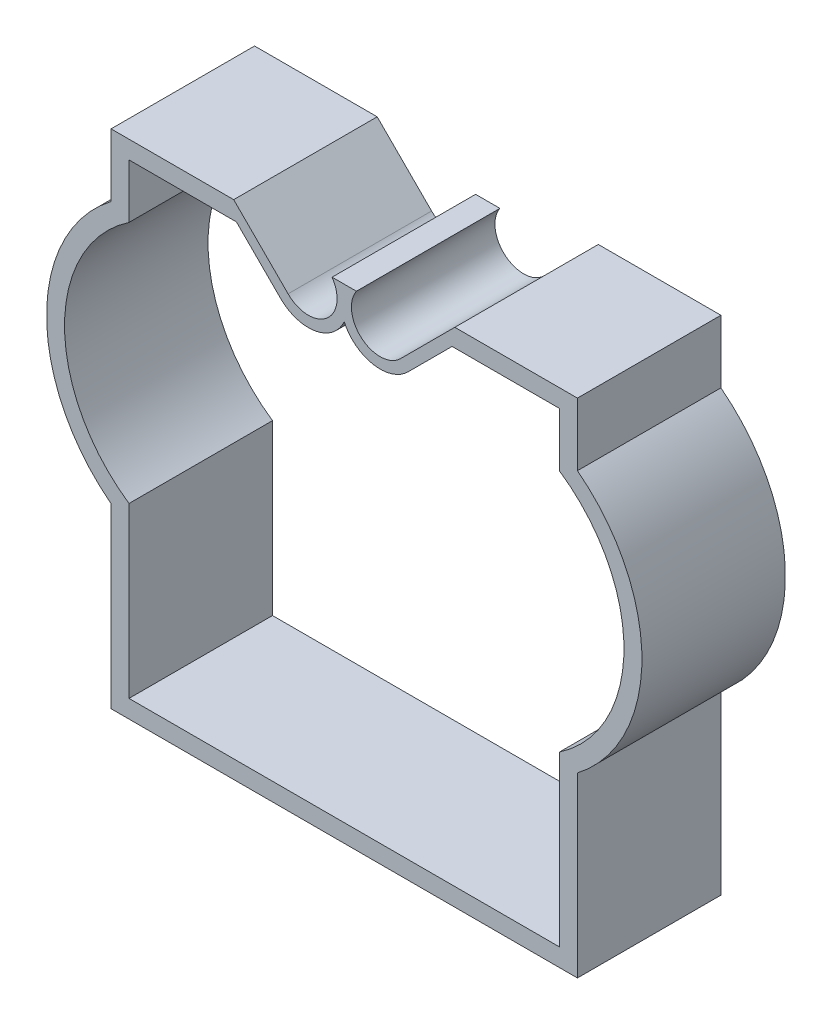
SolidWorks part; units mm, degrees
ref_plane "Ebene vorne" through (0, 0, 0) normal (0, 0, 1) x (1, 0, 0)
ref_plane "Ebene oben" through (0, 0, 0) normal (0, 1, 0) x (1, 0, 0)
ref_plane "Ebene rechts" through (0, 0, 0) normal (1, 0, 0) x (0, 0, -1)
sketch "Skizze1" plane through (0, 0, 0) normal (0, 0, 1) x (1, 0, 0)
  line L0 (-18.4884, 7.993) -> (18.4884, 7.993) construction
  line L1 (-32.5, -35) -> (32.5, -35)
  line L2 (-32.5, -35) -> (-32.5, 35)
  line L3 (-32.5, 35) -> (32.5, 35)
  line L4 (32.5, -35) -> (32.5, 35)
  line L5 (-32.5, -35) -> (32.5, 35) construction
  line L6 (-32.5, 35) -> (-7.4221, 7.993) construction
  line L7 (-30, -32.5) -> (30, -32.5)
  line L8 (-30, -32.5) -> (-30, 32.5)
  line L9 (-30, 32.5) -> (-15.0311, 32.5)
  line L10 (30, -32.5) -> (30, 32.5)
  line L11 (-30, -32.5) -> (30, 32.5) construction
  line L12 (-30, 32.5) -> (-7.3782, 7.993) construction
  line L13 (-1.6456, 1.7722) -> (32.5, -35) construction
  line L14 (-1.6505, 1.7881) -> (30, -32.5) construction
  line L15 (-15.0311, 32.5) -> (-8.8892, 26.3581)
  line L16 (-15.4098, 35) -> (-7.8286, 27.4188)
  line L17 (0, -4.7433) -> (0, -12.0184) construction
  line L18 (15.4098, 35) -> (7.8286, 27.4188)
  line L19 (15.0311, 32.5) -> (8.3305, 25.7994)
  line L20 (15.0311, 32.5) -> (30, 32.5)
  line L21 (-12.9098, 32.5) -> (12.9098, 32.5)
  arc A2 (-12.8129, 30.2818) -> (-3.0992, 25.0861) centre (-18.4884, 7.993) ccw
  circle A3 centre (-18.4884, 7.993) radius 20.5
  circle A4 centre (-5.0001, 30.2472) radius 4
  arc A5 (-1.6505, 1.7881) -> (-1.6456, 1.7722) centre (18.4884, 7.993) ccw
  arc A6 (-0.7993, 0.8659) -> (-0.7961, 0.8574) centre (18.4884, 7.993) ccw
  arc A7 (9.8435, -10.6637) -> (9.9457, -10.7108) centre (18.4884, 7.993) ccw
  arc A8 (10.6947, -11.5859) -> (10.7952, -11.6256) centre (18.4884, 7.993) ccw
  arc A9 (-0.6891, -0.7421) -> (-0.6877, -0.745) centre (18.4884, 7.993) ccw
  arc A10 (-0.3117, -0.3357) -> (-0.3111, -0.337) centre (18.4884, 7.993) ccw
  arc A11 (-8.8892, 26.3581) -> (0, 27.9562) centre (-5.0001, 30.2472) ccw
  circle A12 centre (5.0001, 30.2472) radius 4
  arc A13 (25.747, 27.7275) -> (25.633, 27.7691) centre (18.4884, 7.993) ccw
  arc A14 (25.3776, 27.3297) -> (25.2643, 27.3697) centre (18.4884, 7.993) ccw
  arc A15 (-0.0173, 32.5) -> (10.4978, 30.088) centre (5.0001, 30.2472) cw
  circle A17 centre (18.4884, 7.993) radius 20.5
  arc A18 (-4.532, 26.2747) -> (-9.6274, 29.2176) centre (-18.4884, 7.993) ccw
  arc A19 (0.0173, 32.5) -> (-10.4978, 30.088) centre (-5.0001, 30.2472) ccw
  arc A20 (8.8892, 26.3581) -> (0, 27.9562) centre (5.0001, 30.2472) cw
  arc A21 (12.8129, 30.2818) -> (3.0992, 25.0861) centre (18.4884, 7.993) cw
  point P0 (0, 0)
  point P9 (0, 0)
  point P17 (0, 7.993)
  point P62 (0, 0)
  dimension "D1" = 8
  dimension "D2" = 46
  dimension "D3" = 41
  dimension "D5" = 2.5
  dimension "D6" = 2.5
  dimension "D7" = 65
  dimension "D8" = 60
extrude "Aufsatz-Linear austragen1" add sketch "Skizze1" along normal blind 20
